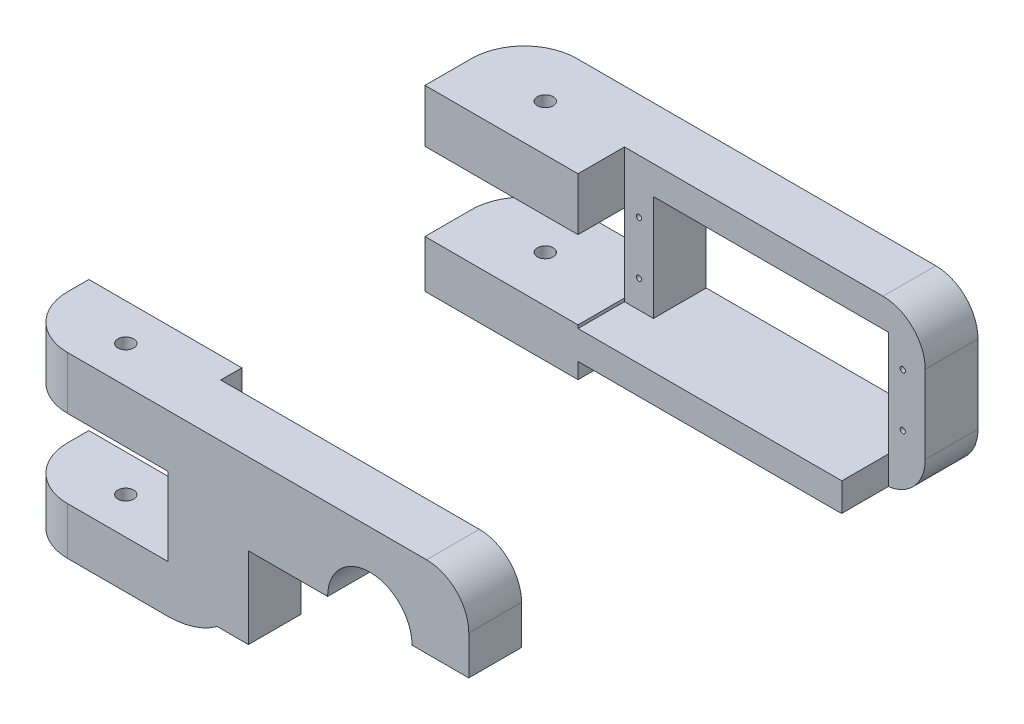
SolidWorks part; units mm, degrees
material "PLA 100% Infill"
ref_plane "Front Plane" through (0, 0, 0) normal (0, 0, 1) x (1, 0, 0)
ref_plane "Top Plane" through (0, 0, 0) normal (0, 1, 0) x (1, 0, 0)
ref_plane "Right Plane" through (0, 0, 0) normal (1, 0, 0) x (0, 0, -1)
sketch "Sketch1" plane through (0, 0, 0) normal (0, 0, 1) x (1, 0, 0)
  line L0 (0, 0) -> (86, 0)
  line L1 (86, -30.8) -> (0, -30.8)
  line L2 (0, -30.8) -> (0, -24.8)
  line L3 (0, -24.8) -> (29, -24.8)
  line L4 (29, -24.8) -> (29, -10)
  line L5 (29, -10) -> (0, -10)
  line L6 (0, -10) -> (0, 0)
  line L7 (86, 0) -> (86, -30.8)
  line L8 (15, -15.4) -> (86, -15.4) construction
  line L9 (0, -30.8) -> (0, -33.8)
  line L10 (0, -33.8) -> (29, -33.8)
  circle A1 centre (67.25, -15.4) radius 8
  arc A2 (29, -33.8) -> (38.3274, -30.8) centre (29, -17.8) ccw
  point P20 (86, -15.4)
  dimension "D1" = 16
  dimension "D9" = 16
  dimension "D2" = 14.8
  dimension "D3" = 10
  dimension "D4" = 18.75
  dimension "D5" = 29
  dimension "D6" = 86
  dimension "D7" = 6
  dimension "D8" = 29
  dimension "D10" = 3
extrude "Boss-Extrude1" add sketch "Sketch1" along normal blind 96.5 contours A1 L8 | L8 A1 | L10 A2 L1 L9
sketch "Sketch2" plane through (0, 0, 0) normal (0, 1, 0) x (1, 0, 0)
  line L0 (86, -96.5) -> (86, 0) construction
  line L1 (86, -10) -> (29, -10)
  line L2 (86, -10) -> (86, -86.5)
  line L3 (86, -86.5) -> (29, -86.5)
  line L4 (29, -10) -> (29, -86.5)
  line L5 (0, -96.5) -> (86, -96.5) construction
  dimension "D1" = 10
  dimension "D2" = 10
  dimension "D3" = 57
extrude "Cut-Extrude1" cut sketch "Sketch2" against normal blind 102
fillet "Fillet1" radius 8 4 edges at (86, 0, 5) (86, -30.8, 5) (86, -30.8, 91.5) (86, 0, 91.5)
sketch "Sketch3" plane through (0, 0, 0) normal (0, 1, 0) x (1, 0, 0)
  line L0 (14, 0) -> (14, -114.5) construction
  line L3 (0, -96.5) -> (0, 0) construction
  line L4 (0, -96.5) -> (78, -96.5) construction
  line L5 (0, 0) -> (78, 0) construction
  circle A0 centre (14, -10) radius 1.5
  circle A1 centre (14, -89.5) radius 1.5
  dimension "D4" = 3
  dimension "D1" = 14
  dimension "D2" = 10
  dimension "D3" = 7
extrude "Cut-Extrude2" cut sketch "Sketch3" against normal through all
sketch "Sketch4" plane through (0, 0, 10) normal (0, 0, 1) x (1, 0, 0)
  line L0 (79, -5.4) -> (34.5, -5.4)
  line L1 (79, -25.4) -> (79, -5.4)
  line L2 (34.5, -25.4) -> (79, -25.4)
  line L3 (34.5, -25.4) -> (34.5, -5.4)
  line L4 (86, -15.4) -> (29, -15.4) construction
  line L5 (86, -22.8) -> (86, -8) construction
  line L7 (31.75, -10.1718) -> (31.75, -20.1718) construction
  line L8 (81.75, -10.1718) -> (81.75, -20.1718) construction
  line L9 (81.75, -20.1718) -> (29, -20.1718) construction
  circle A0 centre (81.75, -20.1718) radius 0.5
  circle A1 centre (81.75, -10.1718) radius 0.5
  circle A2 centre (31.75, -20.1718) radius 0.5
  circle A3 centre (31.75, -10.1718) radius 0.5
  point P1 (69.25, -15.4)
  point P21 (79, -15.4)
  dimension "D1" = 2.75
  dimension "D2" = 20
  dimension "D3" = 44.5
  dimension "D4" = 2.75
  dimension "D5" = 10
  dimension "D6" = 5.2282
  dimension "D7" = 9.75
  dimension "D8" = 7
  dimension "D9" = 10
extrude "Cut-Extrude3" cut sketch "Sketch4" against normal up to next
sketch "Sketch5" plane through (0, 0, 10) normal (0, 0, 1) x (1, 0, 0)
  line L0 (38.3274, -30.8) -> (78, -30.8) construction
  line L2 (79, -25.4) -> (79, -30.8)
  line L3 (79, -30.8) -> (42.4962, -30.8)
  line L5 (34.5, -25.4) -> (79, -25.4) construction
  line L8 (42.4962, -30.8) -> (29, -30.8)
  line L9 (29, -25.4) -> (29, -30.8)
  line L10 (29, -25.4) -> (79, -25.4)
  line L11 (29, -33.8) -> (29, -24.8) construction
  line L12 (79, -25.4) -> (79, -5.4) construction
extrude "Boss-Extrude2" add sketch "Sketch5" along normal blind 8.8
sketch "Sketch6" plane through (0, 0, 96.5) normal (0, 0, 1) x (1, 0, 0)
  line L0 (75.25, -15.4) -> (86, -15.4)
  line L1 (86, -8) -> (86, -22.8) construction
  line L2 (59.25, -15.4) -> (44.25, -15.4)
  line L3 (44.25, -15.4) -> (44.25, -30.8)
  line L4 (78, -30.8) -> (38.3274, -30.8) construction
  line L5 (44.25, -30.8) -> (78, -30.8)
  line L6 (86, -22.8) -> (86, -15.4)
  circle A0 centre (67.25, -15.4) radius 8 construction
  arc A1 (78, -30.8) -> (86, -22.8) centre (78, -22.8) ccw
  arc A2 (59.25, -15.4) -> (75.25, -15.4) centre (67.25, -15.4) ccw
  dimension "D1" = 15
extrude "Cut-Extrude4" cut sketch "Sketch6" against normal blind 10
fillet "Fillet3" radius 10 4 edges at (0, -29.3, 0) (0, -5, 0) (0, -5, 96.5) (0, -29.3, 96.5)
ref_plane "Plane1" through (96, 0, 0) normal (1, 0, 0) x (0, 0, -1)
ref_plane "Plane2" through (0, 0, 106.5) normal (0, 0, 1) x (1, 0, 0)
sketch "Sketch7" plane through (0, 0, 0) normal (0, 1, 0) x (1, 0, 0)
  line L0 (0, -86.5) -> (0, -10) construction
  line L1 (29, -18.8) -> (0, -18.8)
  line L2 (29, -18.8) -> (29, -82.5)
  line L3 (29, -82.5) -> (0, -82.5)
  line L4 (0, -18.8) -> (0, -82.5)
  line L5 (10, -96.5) -> (78, -96.5) construction
  dimension "D1" = 14
extrude "Cut-Extrude5" cut sketch "Sketch7" against normal through all
ref_plane "Plane3" through (0, 0, 41.25) normal (0, 0, 1) x (1, 0, 0)
